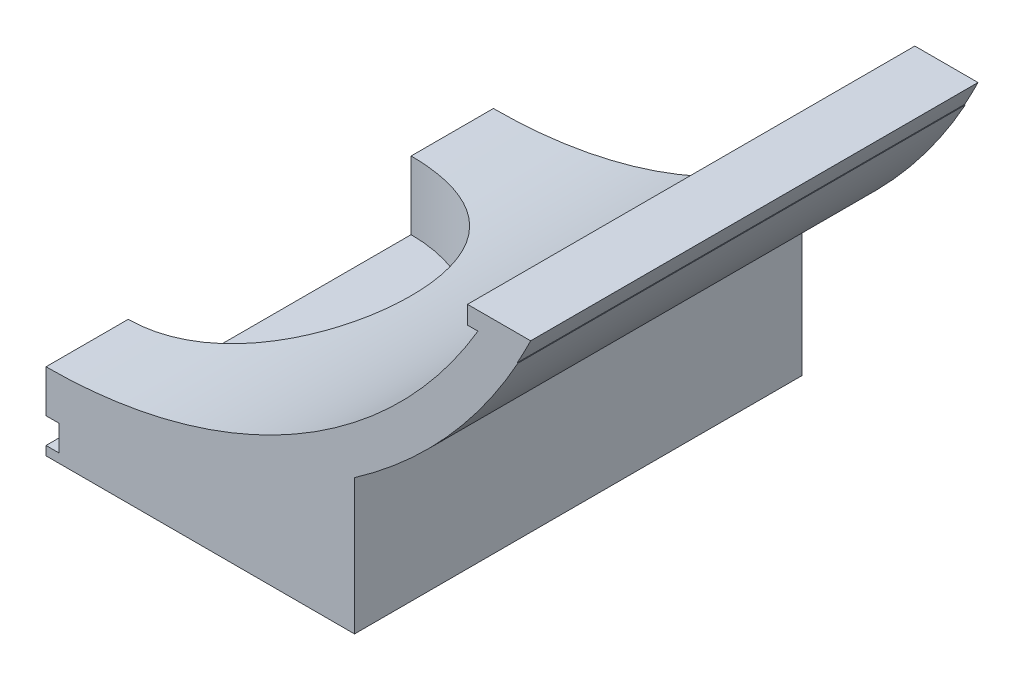
SolidWorks part; units mm, degrees
ref_plane "前视基准面" through (0, 0, 0) normal (0, 0, 1) x (1, 0, 0)
ref_plane "上视基准面" through (0, 0, 0) normal (0, 1, 0) x (1, 0, 0)
ref_plane "右视基准面" through (0, 0, 0) normal (1, 0, 0) x (0, 0, -1)
sketch "草图1" plane through (0, 0, 0) normal (0, 0, 1) x (1, 0, 0)
  arc A0 (-203, 0) -> (203, 0) centre (0, 0) ccw
  arc A1 (-210, 0) -> (210, 0) centre (0, 0) ccw
  arc A2 (-203, 0) -> (203, 0) centre (0, 0) ccw
  circle A3 centre (0, 0) radius 210
  circle A4 centre (0, 0) radius 203
  point P12 (0, 0)
extrude "凸台-拉伸2" add sketch "草图1" along normal blind 174
sketch "草图2" plane through (0, 0, 174) normal (0, 0, 1) x (1, 0, 0)
  line L0 (-173.7354, -102) -> (-170.7354, -102)
  line L1 (-170.7354, -102) -> (-170.7354, -105)
  line L2 (-170.7354, -105) -> (-173.7354, -105)
  line L3 (173.7354, -102) -> (170.7354, -102)
  line L4 (-173.7354, -102) -> (-175.5135, -102)
  line L6 (173.7354, -102) -> (175.5135, -102)
  line L7 (173.7354, -105) -> (170.7354, -105)
  line L8 (170.7354, -105) -> (170.7354, -102)
  circle A0 centre (0, 0) radius 203 construction
  arc A1 (0, -203) -> (-173.7354, -105) centre (0, 0) ccw
  circle M4 centre (0, 0) radius 203
extrude "凸台-拉伸4" add sketch "草图2" against normal up to surface (174 mm away) contours L0 L4 L2 L1 M4 | L8 L7 L6 L3 M4 up to face at (203, 0, 0)
sketch "草图3" plane through (0, 0, 174) normal (0, 0, 1) x (1, 0, 0)
  line L0 (-170.7354, -102) -> (238.3336, -102)
  line L1 (238.3336, -102) -> (254.3342, 272.2925)
  line L2 (254.3342, 272.2925) -> (-334.5694, 221.8511)
  line L3 (-170.7354, -102) -> (-306.8306, -102)
  line L4 (-306.8306, -102) -> (-334.5694, 221.8511)
extrude "切除-拉伸1" cut sketch "草图3" against normal blind 654
ref_plane "基准面1" through (0, -209.75, 0) normal (0, 1, 0) x (1, 0, 0)
sketch "草图5" plane through (0, 0, 174) normal (0, 0, 1) x (1, 0, 0)
  line L0 (0, -209.75) -> (120, -209.75)
  line L1 (95.7, -209.75) -> (-95.7, -209.75) construction
  line L2 (120, -209.75) -> (120, -172.0322)
  line L3 (0, -209.75) -> (-120, -209.75)
  line L4 (-120, -209.75) -> (-120, -172.0322)
  arc A0 (-120, -172.0322) -> (120, -172.0322) centre (0, 0) ccw
  arc M3 (-183.5647, -102) -> (183.5647, -102) centre (0, 0) ccw
extrude "凸台-拉伸5" add sketch "草图5" against normal up to surface (174 mm away) contours L4 L3 M3 | L0 L2 M3 up to face at (0, -129.25, 0)
sketch "草图6" plane through (0, 0, 174) normal (0, 0, 1) x (1, 0, 0)
  line L0 (-175.5135, -102) -> (-166.1957, -102)
  line L1 (175.5135, -102) -> (166.1957, -102)
  arc A0 (-166.1957, -102) -> (166.1957, -102) centre (0, 0) ccw
  arc A1 (-175.5135, -102) -> (175.5135, -102) centre (0, 0) ccw
extrude "凸台-拉伸6" add sketch "草图6" against normal up to surface (174 mm away) up to face at (0, -151.228, 0)
sketch "草图7" plane through (0, 0, 174) normal (0, 0, 1) x (1, 0, 0)
  line L0 (-166.9331, -92) -> (-166.9331, -95)
  line L1 (171.9331, -92) -> (166.9331, -92)
  line L2 (-171.9331, -92) -> (-166.9331, -92)
  line L3 (-188.4969, -92) -> (-171.9331, -92)
  line L4 (171.9331, -92) -> (188.4969, -92)
  line L5 (-166.9331, -95) -> (-170.2939, -95)
  line L6 (166.9331, -92) -> (166.9331, -95)
  line L7 (166.9331, -95) -> (170.2939, -95)
  arc A1 (-188.4969, -92) -> (188.4969, -92) centre (0, 0) ccw
  arc A2 (-170.2939, -95) -> (170.2939, -95) centre (0, 0) ccw
extrude "凸台-拉伸7" add sketch "草图7" against normal up to surface (174 mm away) up to face at (0, -169.2192, 0)
sketch "草图8" plane through (0, 0, 0) normal (0, 0, -1) x (-1, 0, 0)
  line L0 (166.9331, -92) -> (163.9331, -92)
  line L1 (163.9331, -92) -> (163.9331, -99)
  line L2 (163.9331, -99) -> (168, -99)
  line L3 (166.9331, -92) -> (166.9331, -95)
  line L4 (166.9331, -95) -> (170.2939, -95)
  line L6 (-166.9331, -95) -> (-170.2939, -95)
  line L7 (-166.9331, -92) -> (-166.9331, -95)
  line L8 (-163.9331, -99) -> (-168, -99)
  line L9 (-163.9331, -92) -> (-163.9331, -99)
  line L10 (-166.9331, -92) -> (-163.9331, -92)
  arc A0 (-170.2939, -95) -> (170.2939, -95) centre (0, 0) ccw construction
  arc A1 (168, -99) -> (170.2939, -95) centre (0, 0) ccw
  arc A2 (-168, -99) -> (-170.2939, -95) centre (0, 0) cw
extrude "凸台-拉伸8" add sketch "草图8" against normal up to surface (174 mm away) up to face at (0, -135.959, 174)
sketch "草图9" plane through (0, 0, 174) normal (0, 0, 1) x (1, 0, 0)
  line L0 (0, -195) -> (0, -225)
  line L1 (0, -225) -> (120, -225)
  line L2 (120, -225) -> (120, -209.75)
  line L3 (120, -209.75) -> (-120, -209.75)
  line L4 (-120, -209.75) -> (-120, -225)
  line L5 (-120, -225) -> (18.0074, -225)
  arc A2 (-168, -99) -> (168, -99) centre (0, 0) ccw construction
  line M11 (-120, -209.75) -> (-10.2439, -209.75)
  arc M12 (-10.2439, -209.75) -> (10.2439, -209.75) centre (0, 0) ccw
  line M13 (10.2439, -209.75) -> (120, -209.75)
extrude "凸台-拉伸9" add sketch "草图9" against normal up to vertex (174 mm away) contours L1 L2 L0 M13 M12 | L4 L5 L0 M12 M11 up to point (120, -209.75, 0)
sketch "草图10" plane through (0, 0, 174) normal (0, 0, 1) x (1, 0, 0)
  line L0 (-5, -221.5) -> (-5, -211.5)
  line L2 (0, -211.5) -> (5, -211.5)
  line L3 (-55, -195) -> (-55, -221.5)
  line L4 (-5, -211.5) -> (0, -211.5)
  line L8 (5, -211.5) -> (5, -221.5)
  line L9 (5, -221.5) -> (-5, -221.5)
sketch "草图11" plane through (0, 0, 0) normal (0, 1, 0) x (1, 0, 0)
  line L0 (-163.9331, -87) -> (188.4969, -87)
  line L1 (-163.9331, -174) -> (-163.9331, 0) construction
  line L2 (188.4969, 0) -> (188.4969, -174) construction
  line L3 (0, 0) -> (0, -137.3076)
  circle A0 centre (0, -87) radius 55
extrude "切除-拉伸4" cut sketch "草图11" against normal up to vertex (221.5 mm away) up to point (-55, -221.5, 174)
extrude "切除-拉伸5" cut sketch "草图10" against normal blind 87 contours L9 L8 L2 L4 L0
sketch "草图13" plane through (0, 0, 0) normal (1, 0, 0) x (0, 0, -1)
  line L1 (-205.4978, -60.5834) -> (46.8817, -60.5834)
  line L2 (-205.4978, -60.5834) -> (-205.4978, -258.0797)
  line L3 (-205.4978, -258.0797) -> (46.8817, -258.0797)
  line L4 (46.8817, -60.5834) -> (46.8817, -258.0797)
extrude "切除-拉伸6" cut sketch "草图13" against normal blind 244
